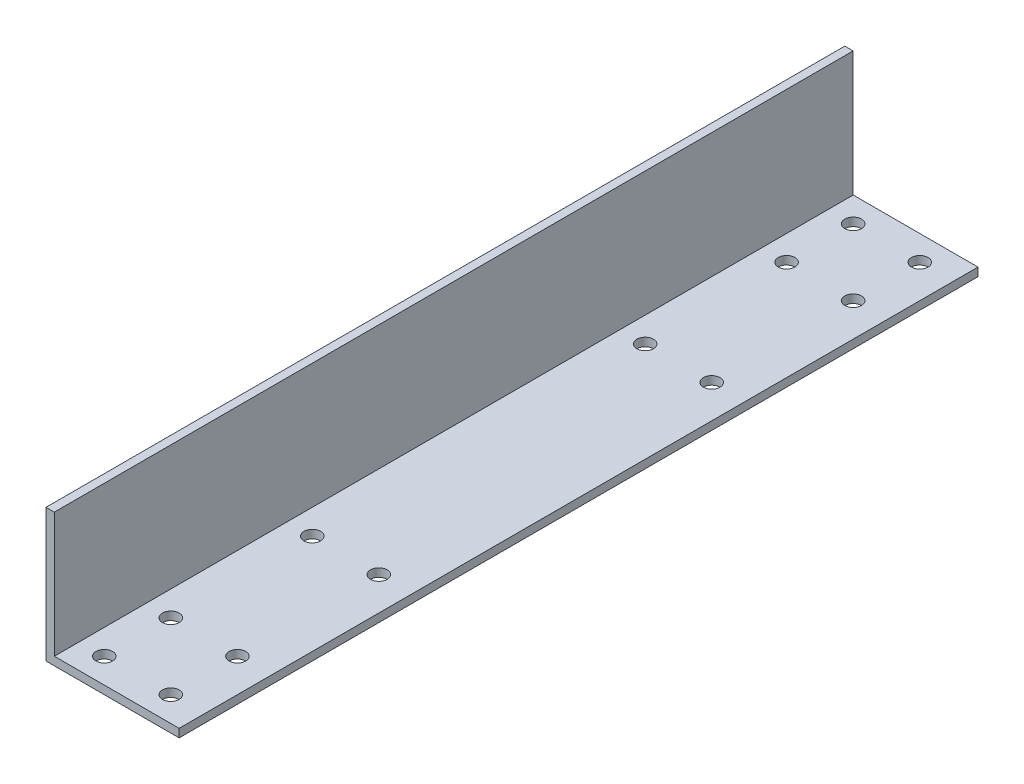
SolidWorks part; units mm, degrees
ref_plane "Front Plane" through (0, 0, 0) normal (0, 0, 1) x (1, 0, 0)
ref_plane "Top Plane" through (0, 0, 0) normal (0, 1, 0) x (1, 0, 0)
ref_plane "Right Plane" through (0, 0, 0) normal (1, 0, 0) x (0, 0, -1)
sketch "Sketch1" plane through (0, 0, 0) normal (0, 0, 1) x (1, 0, 0)
  line L0 (0, 0) -> (50.8, 0)
  line L1 (50.8, 0) -> (50.8, 3.175)
  line L2 (50.8, 3.175) -> (3.175, 3.175)
  line L3 (3.175, 3.175) -> (3.175, 50.8)
  line L4 (3.175, 50.8) -> (0, 50.8)
  line L5 (0, 50.8) -> (0, 0)
  dimension "D1" = 50.8
  dimension "D2" = 50.8
  dimension "D3" = 3.175
  dimension "D4" = 3.175
extrude "Boss-Extrude1" add sketch "Sketch1" along normal blind 304.8
sketch "Sketch2" plane through (0, 0, 0) normal (0, -1, 0) x (1, 0, 0)
  line L0 (0, 0) -> (50.8, 0) construction
  line L1 (0, 304.8) -> (0, 0) construction
  line L2 (0, 152.4) -> (50.8, 152.4)
  line L3 (50.8, 304.8) -> (50.8, 0) construction
  circle A0 centre (38.1, 9.525) radius 3.175
  circle A1 centre (12.7, 9.525) radius 3.175
  circle A2 centre (38.1, 34.925) radius 3.175
  circle A3 centre (12.7, 34.925) radius 3.175
  circle A4 centre (38.1, 88.9) radius 3.175
  circle A5 centre (12.7, 88.9) radius 3.175
  circle A6 centre (38.1, 269.875) radius 3.175
  circle A7 centre (38.1, 295.275) radius 3.175
  circle A8 centre (12.7, 295.275) radius 3.175
  circle A9 centre (12.7, 269.875) radius 3.175
  circle A10 centre (38.1, 215.9) radius 3.175
  circle A11 centre (12.7, 215.9) radius 3.175
  point P16 (38.1, 138.4622)
  point P21 (12.7, 138.4622)
  dimension "D1" = 6.35
  dimension "D2" = 6.35
  dimension "D3" = 6.35
  dimension "D4" = 6.35
  dimension "D9" = 6.35
  dimension "D10" = 6.35
  dimension "D13" = 12.7
  dimension "D5" = 25.4
  dimension "D6" = 25.4
  dimension "D7" = 9.525
  dimension "D8" = 12.7
  dimension "D11" = 25.4
  dimension "D12" = 63.5
extrude "Cut-Extrude1" cut sketch "Sketch2" against normal through all contours A1 | A3 | A2 | A0 | A11 | A10 | A4 | A5 | A8 | A9 | A6 | A7
